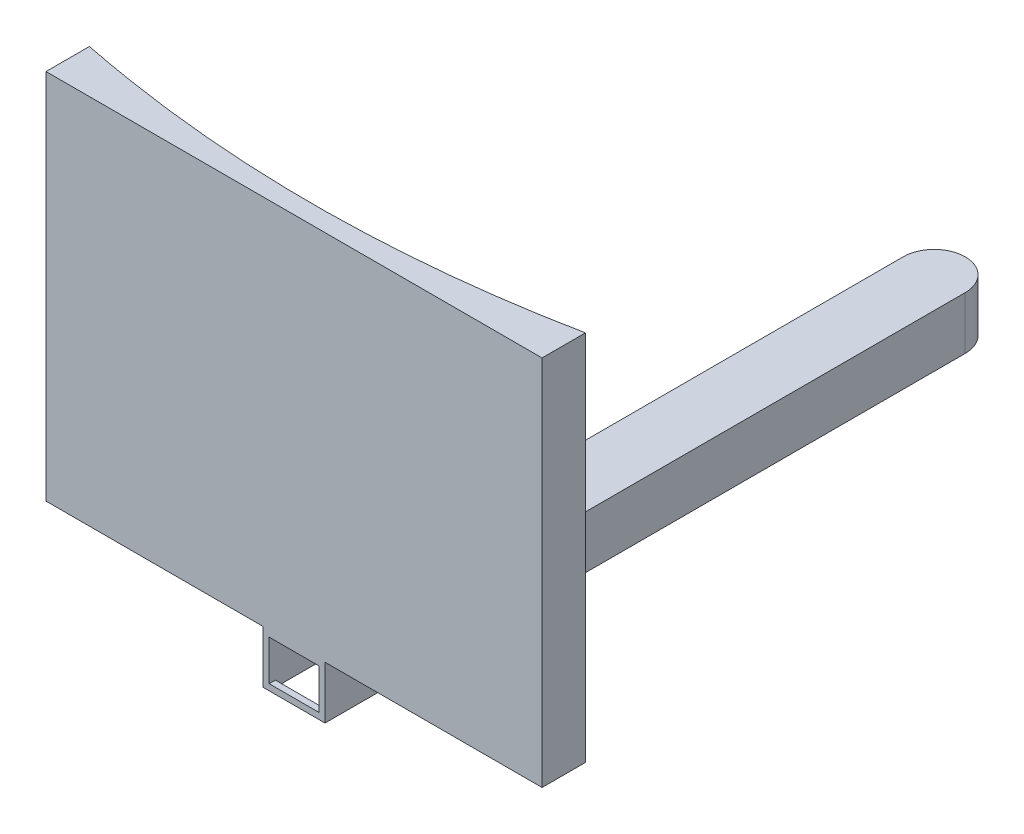
SolidWorks part; units mm, degrees
ref_plane "Front Plane" through (0, 0, 0) normal (0, 0, 1) x (1, 0, 0)
ref_plane "Top Plane" through (0, 0, 0) normal (0, 1, 0) x (1, 0, 0)
ref_plane "Right Plane" through (0, 0, 0) normal (1, 0, 0) x (0, 0, -1)
sketch "Sketch1" plane through (0, 0, 0) normal (0, 1, 0) x (1, 0, 0)
  line L0 (0, -200) -> (0, 0) construction
  line L1 (-225, -136.7187) -> (225, -136.7187) construction
  parabola Q0 (-225, -136.7187) -> (225, -136.7187) focus (0, 0) apex (0, -200) construction
  spline S0 degree 1 poles (-225.2451, -137.1545) (225.2451, -137.1545) knots 0 0 1 1 construction
  spline S1 degree 3 poles (-225.2451, -137.1545) (-222.9082, -138.4691) (-218.2041, -141.0739) (-208.8273, -146.1009) (-197.0951, -152.0818) (-183.0206, -158.7616) (-164.2523, -167.0094) (-140.7912, -176.0823) (-112.6357, -184.9909) (-84.4784, -191.9202) (-46.9336, -198.52) (0, -201.82) (46.9336, -198.52) (84.4784, -191.9202) (112.6357, -184.9909) (140.7912, -176.0823) (164.2523, -167.0094) (183.0206, -158.7616) (197.0951, -152.0818) (208.8273, -146.1009) (218.2041, -141.0739) (222.9082, -138.4691) (225.2451, -137.1545) knots 0.496023 0.496023 0.496023 0.496023 0.496147 0.496271 0.49652 0.496768 0.497017 0.497514 0.498011 0.498508 0.499006 0.5 0.500994 0.501492 0.501989 0.502486 0.502983 0.503232 0.50348 0.503729 0.503853 0.503977 0.503977 0.503977 0.503977 construction
  dimension "D1" = 450
  dimension "D2" = 200
  dimension "D3" = 0.5
sketch "Sketch4" plane through (0, 0, 0) normal (0, 1, 0) x (1, 0, 0)
  line L0 (-80, -157.049) -> (-80, -357.049) construction
  line L1 (80, -173.7313) -> (80, -373.7313) construction
  line L2 (0, -200) -> (0, 0) construction
  line L3 (-80, -192.5099) -> (-80, -206.5)
  line L4 (80, -192.5099) -> (80, -206.5)
  line L5 (-80, -206.5) -> (80, -206.5)
  spline S0 degree 3 poles (1573.6078, -1009.9911) (-454.8299, 36.4001) (-329.3751, -81.4734) (-208.8273, -146.1009) (-197.0951, -152.0818) (-183.0206, -158.7616) (-164.2523, -167.0094) (-140.7912, -176.0823) (-112.6357, -184.9909) (-84.4784, -191.9202) (-46.9336, -198.52) (0, -201.82) (46.9336, -198.52) (84.4784, -191.9202) (112.6357, -184.9909) (140.7912, -176.0823) (164.2523, -167.0094) (183.0206, -158.7616) (197.0951, -152.0818) (208.8273, -146.1009) (329.3765, -81.4727) (454.8329, 36.4029) (-1573.6829, -1010.0298) knots 0.490128 0.490128 0.490128 0.490128 0.496147 0.496271 0.49652 0.496768 0.497017 0.497514 0.498011 0.498508 0.499006 0.5 0.500994 0.501492 0.501989 0.502486 0.502983 0.503232 0.50348 0.503729 0.503853 0.509872 0.509872 0.509872 0.509872 only from (-225.2451, -137.1545) to (225.2451, -137.1545) construction
  spline S1 degree 3 poles (-80, -192.5099) (-72.1067, -194.0866) (-45.4407, -198.6249) (0, -201.82) (45.4407, -198.6249) (72.1067, -194.0866) (80, -192.5099) knots 0.498588 0.498588 0.498588 0.498588 0.499006 0.5 0.500994 0.501412 0.501412 0.501412 0.501412
  point P2 (0, -206.5)
  point P3 (0, 0)
  point P13 (0, 0)
  point P14 (0, -200.5)
  dimension "D2" = 80
  dimension "D3" = 80
  dimension "D1" = 6
extrude "Boss-Extrude3" add sketch "Sketch4" along normal blind 120
sketch "Sketch6" plane through (0, 0, 0) normal (0, -1, 0) x (1, 0, 0)
  line L0 (10, 0) -> (10, 206.5)
  line L1 (-80, 206.5) -> (80, 206.5) construction
  line L2 (10, 206.5) -> (-10, 206.5)
  line L3 (-10, 206.5) -> (-10, 0)
  line L4 (0, 200) -> (0, 0) construction
  arc A0 (10, 0) -> (-10, 0) centre (0, 0) cw
  point P9 (0, 0)
  point P10 (0, 0)
  dimension "D1" = 10
extrude "Boss-Extrude4" add sketch "Sketch6" along normal blind 2
sketch "Sketch7" plane through (0, -2, 0) normal (0, -1, 0) x (1, 0, 0)
  line L0 (8, 0) -> (8, 204.5)
  line L1 (8, 204.5) -> (-8, 204.5)
  line L2 (-8, 204.5) -> (-8, 0)
  line L3 (10, 0) -> (10, 206.5)
  line L4 (10, 206.5) -> (-10, 206.5)
  line L5 (-10, 206.5) -> (-10, 0)
  line L6 (10, 0) -> (10, 206.5)
  line L7 (10, 206.5) -> (-10, 206.5)
  line L8 (-10, 206.5) -> (-10, 0)
  arc A0 (-8, 0) -> (8, 0) centre (0, 0) ccw
  arc A1 (-10, 0) -> (10, 0) centre (0, 0) ccw
  arc A2 (-10, 0) -> (10, 0) centre (0, 0) ccw
  dimension "D1" = 0
  dimension "D2" = 2
extrude "Boss-Extrude5" add sketch "Sketch7" along normal blind 15
sketch "Sketch8" plane through (0, 0, 206.5) normal (0, 0, 1) x (1, 0, 0)
  line L0 (8, -15) -> (-8, -15)
  line L1 (10, -17) -> (-10, -17) construction
  line L2 (10, -17) -> (10, 0) construction
  line L3 (10, 0) -> (-10, 0) construction
  line L4 (-10, -17) -> (-10, 0) construction
  line L5 (-8, -15) -> (-8, -2)
  line L6 (8, -2) -> (-8, -2)
  line L7 (8, -15) -> (8, -2)
  dimension "D1" = 2
extrude "Cut-Extrude2" cut sketch "Sketch8" against normal blind 15
equation "\"Focus\"= 200mm"
equation "\"Dish Width\"= 450mm"
equation "\"Plate Thickness\"= 0.5mm"
equation "\"D1@Sketch1\"=\"Dish Width\""
equation "\"D2@Sketch1\"=\"Focus\""
equation "\"D3@Sketch1\"=\"Plate Thickness\""
equation "\"D3@Sketch4\"=\"D2@Sketch4\""
